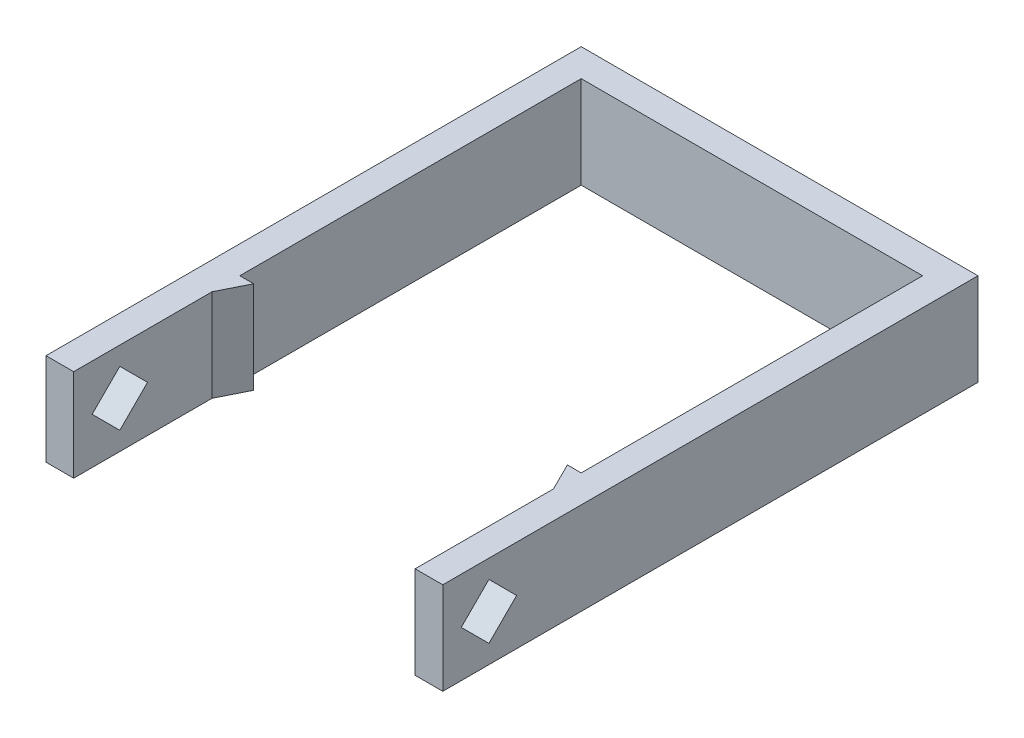
SolidWorks part; units mm, degrees
ref_plane "Front Plane" through (0, 0, 0) normal (0, 0, 1) x (1, 0, 0)
ref_plane "Top Plane" through (0, 0, 0) normal (0, 1, 0) x (1, 0, 0)
ref_plane "Right Plane" through (0, 0, 0) normal (1, 0, 0) x (0, 0, -1)
sketch "Sketch1" plane through (0, 0, 0) normal (0, 1, 0) x (1, 0, 0)
  line L0 (0, 18.5) -> (0, 21.5) construction
  line L1 (-18.5, -18.5) -> (18.5, -18.5) construction
  line L2 (-18.5, -18.5) -> (-18.5, 18.5)
  line L3 (-18.5, 18.5) -> (18.5, 18.5)
  line L4 (18.5, -18.5) -> (18.5, 18.5)
  line L5 (-18.5, -18.5) -> (18.5, 18.5) construction
  line L6 (-18.5, 18.5) -> (18.5, -18.5) construction
  line L7 (-21.5, -21.5) -> (-18.5, -21.5)
  line L8 (-21.5, -21.5) -> (-21.5, 21.5)
  line L9 (-21.5, 21.5) -> (21.5, 21.5)
  line L10 (21.5, -21.5) -> (21.5, 21.5)
  line L11 (-21.5, -21.5) -> (21.5, 21.5) construction
  line L12 (-21.5, 21.5) -> (21.5, -21.5) construction
  line L13 (-18.5, -21.5) -> (-17, -18.5)
  line L14 (18.5, -21.5) -> (21.5, -21.5)
  line L15 (18.5, -21.5) -> (18.5, -36.5)
  line L16 (-18.5, -18.5) -> (-18.5, -21.5)
  line L17 (18.5, -18.5) -> (18.5, -21.5)
  line L18 (18.5, -21.5) -> (21.5, -21.5)
  line L19 (18.5, -36.5) -> (21.5, -36.5)
  line L20 (21.5, -21.5) -> (21.5, -36.5)
  line L21 (-21.5, -21.5) -> (-18.5, -21.5)
  line L22 (-21.5, -21.5) -> (-21.5, -36.5)
  line L23 (-21.5, -36.5) -> (-18.5, -36.5)
  line L24 (-18.5, -21.5) -> (-18.5, -36.5)
  line L25 (-17, -18.5) -> (-18.5, -18.5)
  line L26 (18.5, -21.5) -> (17, -18.5)
  line L27 (17, -18.5) -> (18.5, -18.5)
  point P0 (0, 0)
  point P6 (0, 0)
  dimension "D1" = 3
  dimension "D2" = 37
  dimension "D3" = 15
  dimension "D4" = 1.5
extrude "Boss-Extrude1" add sketch "Sketch1" along normal blind 10 contours L4 L17 L14 L10 L9 L8 L7 L16 L2 L3 | L24 L7 L22 L23 | L20 L14 L15 L19 | L13 L25 L16 | L27 L26 L17
sketch "Sketch3" plane through (21.5, 0, 0) normal (1, 0, 0) x (0, 0, -1)
  line L0 (-31.5, 8) -> (-34.5, 5)
  line L1 (-31.5, 8) -> (-28.5, 5)
  line L2 (-34.5, 5) -> (-31.5, 2)
  line L3 (-28.5, 5) -> (-31.5, 2)
  line L4 (-31.5, 8) -> (-31.5, 2) construction
  line L5 (-34.5, 5) -> (-28.5, 5) construction
  line L6 (-36.5, 10) -> (-36.5, 0) construction
  line L7 (-31.5, 2) -> (-31.5, 0) construction
  line L8 (-36.5, 0) -> (21.5, 0) construction
  line L9 (-31.5, 8) -> (-31.5, 10) construction
  line L10 (-36.5, 10) -> (21.5, 10) construction
  line L11 (-34.5, 5) -> (-36.5, 5) construction
  point P1 (-31.5, 5)
  dimension "D1" = 2
extrude "Cut-Extrude1" cut sketch "Sketch3" against normal through all
